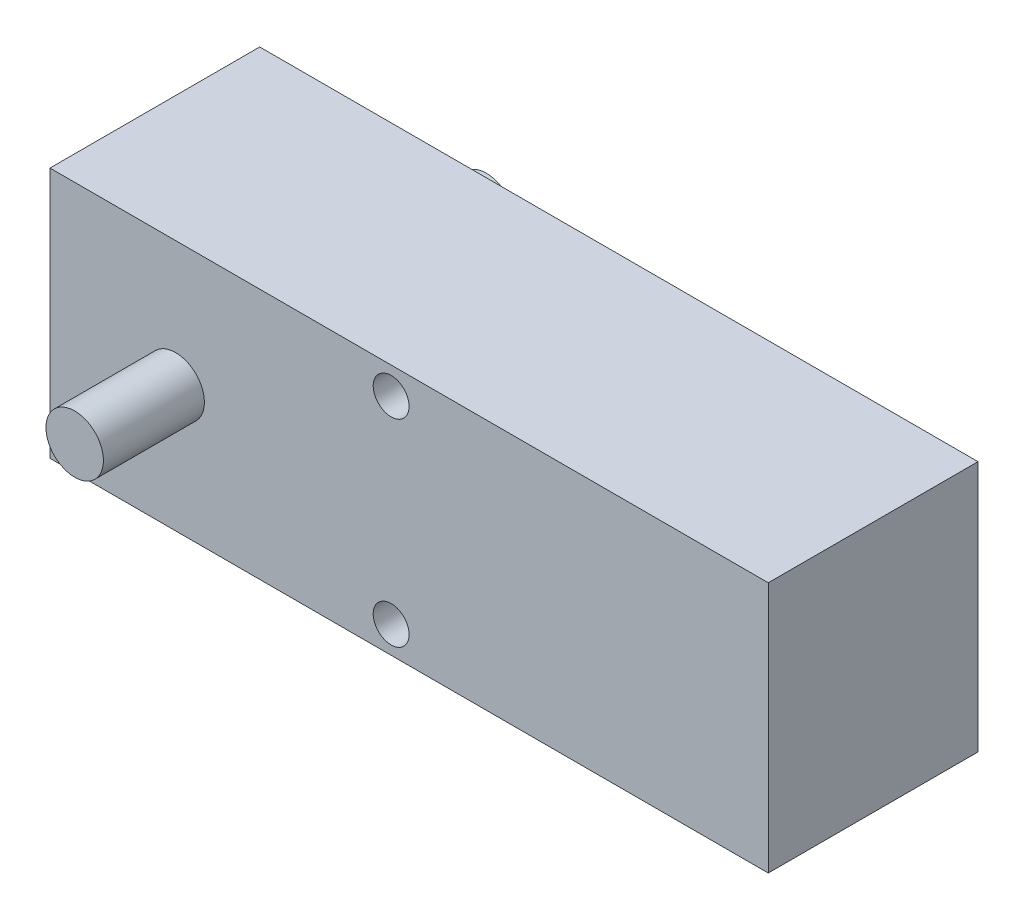
SolidWorks part; units mm, degrees
ref_plane "Front Plane" through (0, 0, 0) normal (0, 0, 1) x (1, 0, 0)
ref_plane "Top Plane" through (0, 0, 0) normal (0, 1, 0) x (1, 0, 0)
ref_plane "Right Plane" through (0, 0, 0) normal (1, 0, 0) x (0, 0, -1)
sketch "Sketch1" plane through (0, 0, 0) normal (0, 0, 1) x (1, 0, 0)
  circle A0 centre (0, 0) radius 2.54
  dimension "D1" = 5.08
extrude "Boss-Extrude1" add sketch "Sketch1" along normal mid plane 36.3982
sketch "Sketch2" plane through (0, 0, 0) normal (0, 0, 1) x (1, 0, 0)
  line L0 (0, 0) -> (-11.1125, 0) construction
  line L1 (-11.1125, 11.1125) -> (52.3875, 11.1125)
  line L2 (-11.1125, 11.1125) -> (-11.1125, -11.1125)
  line L3 (-11.1125, -11.1125) -> (52.3875, -11.1125)
  line L4 (52.3875, 11.1125) -> (52.3875, -11.1125)
  dimension "D1" = 63.5
  dimension "D2" = 22.225
  dimension "D3" = 11.1125
extrude "Boss-Extrude2" add sketch "Sketch2" along normal mid plane 18.542
sketch "Sketch3" plane through (0, 0, 9.271) normal (0, 0, 1) x (1, 0, 0)
  line L0 (0, 0) -> (19.05, 0) construction
  line L1 (19.05, 8.7312) -> (19.05, -8.7313) construction
  circle A0 centre (19.05, -8.7313) radius 1.5875
  circle A1 centre (19.05, 8.7312) radius 1.5875
  point P6 (19.05, 0)
  dimension "D1" = 3.175
  dimension "D2" = 17.4625
  dimension "D3" = 19.05
extrude "Cut-Extrude1" cut sketch "Sketch3" against normal through all both and the other way through all
